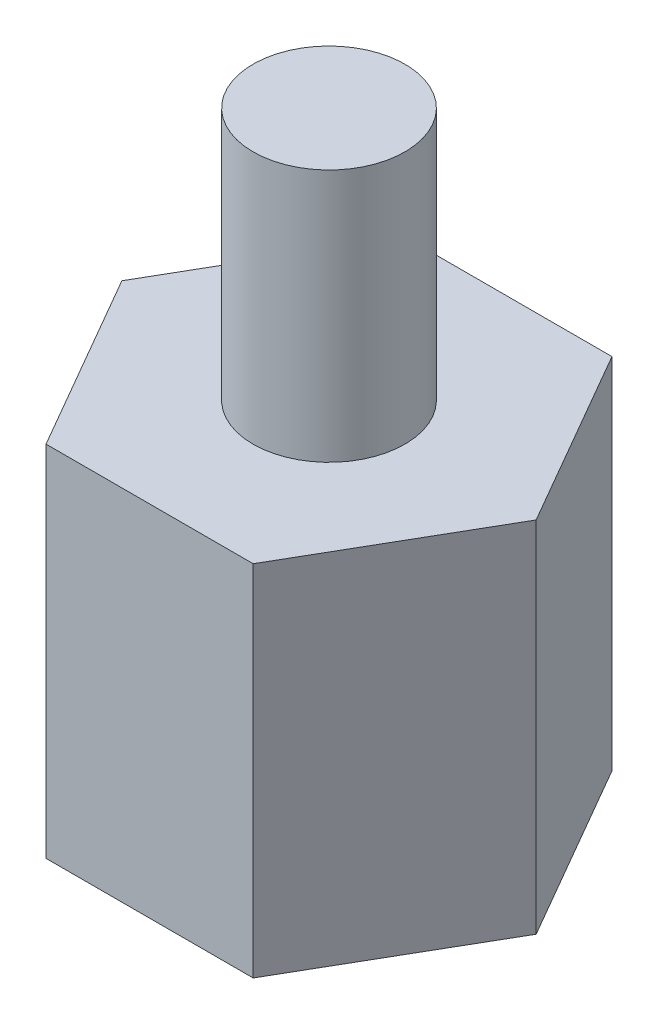
SolidWorks part; units mm, degrees
material "Nylon 6/10"
ref_plane "Front Plane" through (0, 0, 0) normal (0, 0, 1) x (1, 0, 0)
ref_plane "Top Plane" through (0, 0, 0) normal (0, 1, 0) x (1, 0, 0)
ref_plane "Right Plane" through (0, 0, 0) normal (1, 0, 0) x (0, 0, -1)
sketch "Sketch1" plane through (0, 0, 0) normal (0, 1, 0) x (1, 0, 0)
  line L1 (3.6368, 0) -> (1.8184, 3.1496)
  line L2 (1.8184, 3.1496) -> (-1.8184, 3.1496)
  line L3 (-1.8184, 3.1496) -> (-3.6368, 0)
  line L4 (-3.6368, 0) -> (-1.8184, -3.1496)
  line L5 (-1.8184, -3.1496) -> (1.8184, -3.1496)
  line L6 (1.8184, -3.1496) -> (3.6368, 0)
  circle A0 centre (0, 0) radius 3.1496 construction
  dimension "D1" = 6.2992
extrude "Boss-Extrude1" add sketch "Sketch1" along normal blind 6.2992
sketch "Sketch2" plane through (0, 6.2992, 0) normal (0, 1, 0) x (-1, 0, 0)
  circle A0 centre (0, 0) radius 1.3335
  dimension "D1" = 2.667
extrude "Boss-Extrude2" add sketch "Sketch2" along normal blind 4.445
sketch "Sketch3" plane through (0, 0, 0) normal (0, -1, 0) x (1, 0, 0)
  circle A0 centre (0, 0) radius 1.27
  dimension "D1" = 2.54
extrude "Cut-Extrude1" cut sketch "Sketch3" against normal blind 3.81
